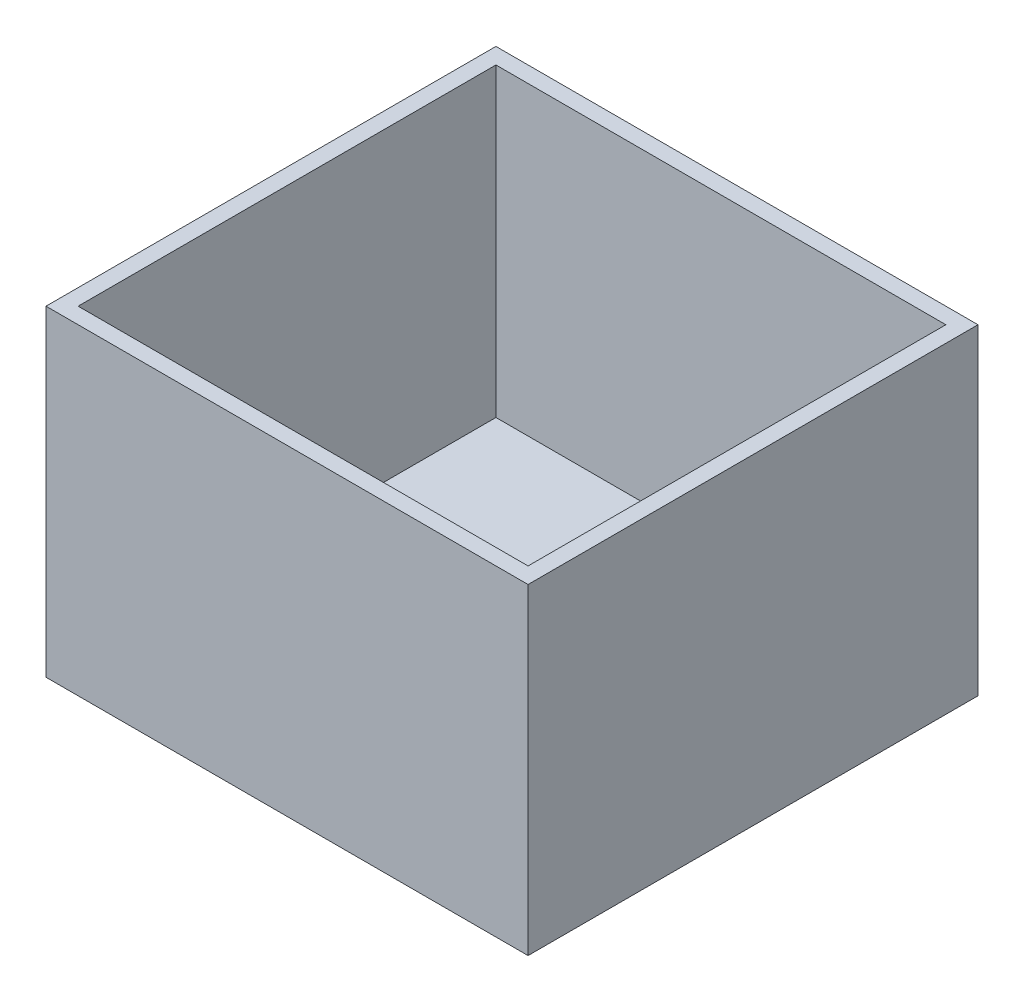
SolidWorks part; units mm, degrees
ref_plane "Front Plane" through (0, 0, 0) normal (0, 0, 1) x (1, 0, 0)
ref_plane "Top Plane" through (0, 0, 0) normal (0, 1, 0) x (1, 0, 0)
ref_plane "Right Plane" through (0, 0, 0) normal (1, 0, 0) x (0, 0, -1)
sketch "Sketch2" plane through (0, 0, 0) normal (0, 1, 0) x (1, 0, 0)
  line L0 (12.7, 33.02) -> (35.56, 33.02)
  line L1 (-35.56, 33.02) -> (-12.7, 33.02)
  line L2 (35.56, 33.02) -> (35.56, 12.7)
  line L3 (35.56, -33.02) -> (-35.56, -33.02)
  line L4 (-35.56, 33.02) -> (-35.56, 12.7)
  line L5 (-12.7, 33.02) -> (-35.56, 12.7) construction
  line L6 (12.7, 33.02) -> (35.56, 12.7) construction
  line L7 (-12.7, 33.02) -> (12.7, 33.02)
  line L8 (-35.56, 12.7) -> (-35.56, -33.02)
  line L9 (35.56, 12.7) -> (35.56, -33.02)
  line L10 (-38.1, 35.56) -> (-12.7, 35.56)
  line L11 (-12.7, 35.56) -> (12.7, 35.56)
  line L12 (12.7, 35.56) -> (38.1, 35.56)
  line L13 (38.1, 35.56) -> (38.1, 12.7)
  line L14 (38.1, 12.7) -> (38.1, -35.56)
  line L15 (38.1, -35.56) -> (-38.1, -35.56)
  line L16 (-38.1, 12.7) -> (-38.1, -35.56)
  line L17 (-38.1, 35.56) -> (-38.1, 12.7)
  point P3 (-35.56, 12.7)
  point P7 (0, -33.02)
  point P9 (35.56, 12.7)
  point P10 (12.7, 33.02)
  point P11 (-12.7, 33.02)
  dimension "D1" = 66.04
  dimension "D2" = 71.12
  dimension "D3" = 20.32
  dimension "D4" = 12.7
  dimension "D5" = 12.7
  dimension "D6" = 33.02
  dimension "D7" = 2.54
extrude "Boss-Extrude1" add sketch "Sketch2" along normal mid plane 50.8
shell "Shell1" thickness 2.54
